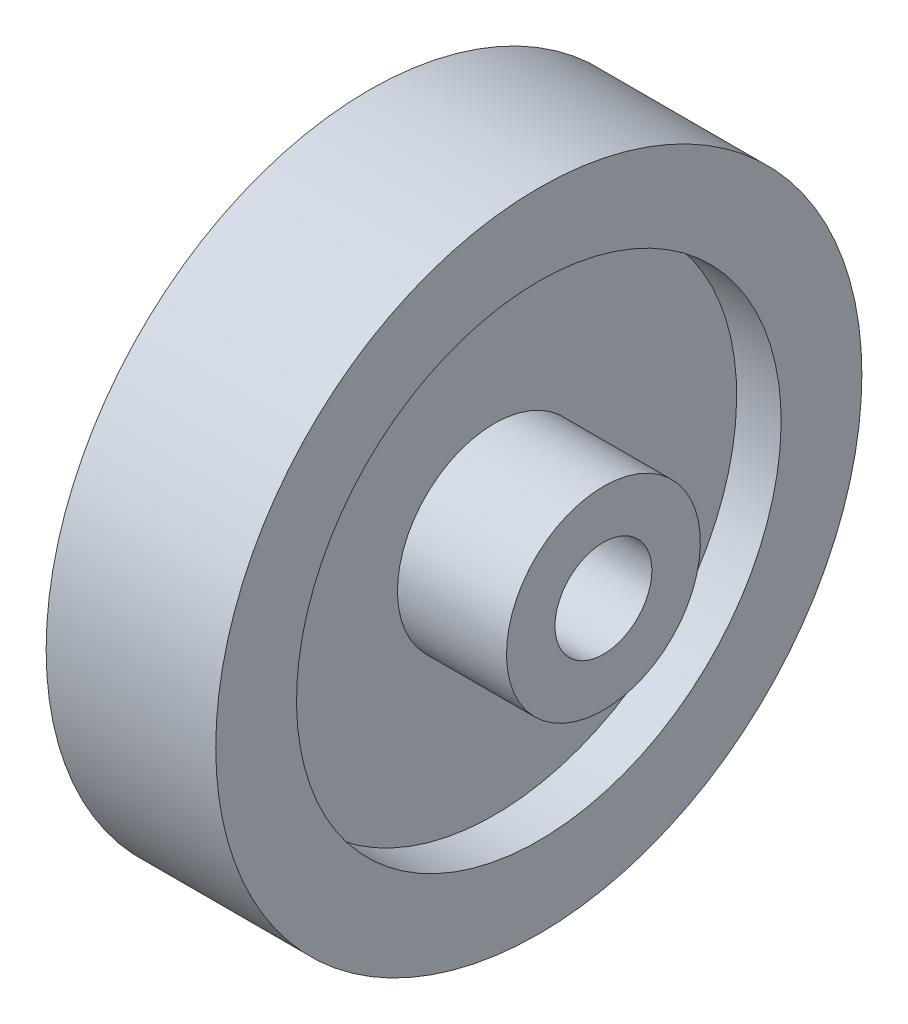
SolidWorks part; units mm, degrees
ref_plane "Front" through (0, 0, 0) normal (0, 0, 1) x (1, 0, 0)
ref_plane "Top" through (0, 0, 0) normal (0, 1, 0) x (1, 0, 0)
ref_plane "Right" through (0, 0, 0) normal (1, 0, 0) x (0, 0, -1)
sketch "Esquisse1" plane through (0, 0, 0) normal (0, 0, 1) x (1, 0, 0)
  line L0 (18.5, 6) -> (-18.5, 6)
  line L1 (0, 0) -> (-18.5, 0) construction
  line L2 (0, 0) -> (0, 40) construction
  line L3 (0, 40) -> (-18.5, 40) construction
  line L4 (-18.5, 0) -> (-18.5, 40) construction
  line L5 (-18.5, 6) -> (-18.5, 12)
  line L7 (5, 12) -> (5, 30)
  line L8 (-5, 30) -> (-10.5, 30)
  line L9 (-10.5, 30) -> (-10.5, 40)
  line L10 (-10.5, 40) -> (10.5, 40)
  line L11 (18.5, 6) -> (18.5, 12)
  line L13 (10.5, 30) -> (10.5, 40)
  line L14 (5, 30) -> (10.5, 30)
  line L15 (-5, 12) -> (-5, 30)
  line L16 (-18.5, 12) -> (-5, 12)
  line L17 (5, 12) -> (18.5, 12)
  point P14 (0, 6)
  dimension "D1" = 40
  dimension "D2" = 21
  dimension "D3" = 6
  dimension "D4" = 18.5
  dimension "D5" = 10
  dimension "D6" = 10
  dimension "D7" = 12
revolve "Révolution1" add sketch "Esquisse1" angle 360 about L1
